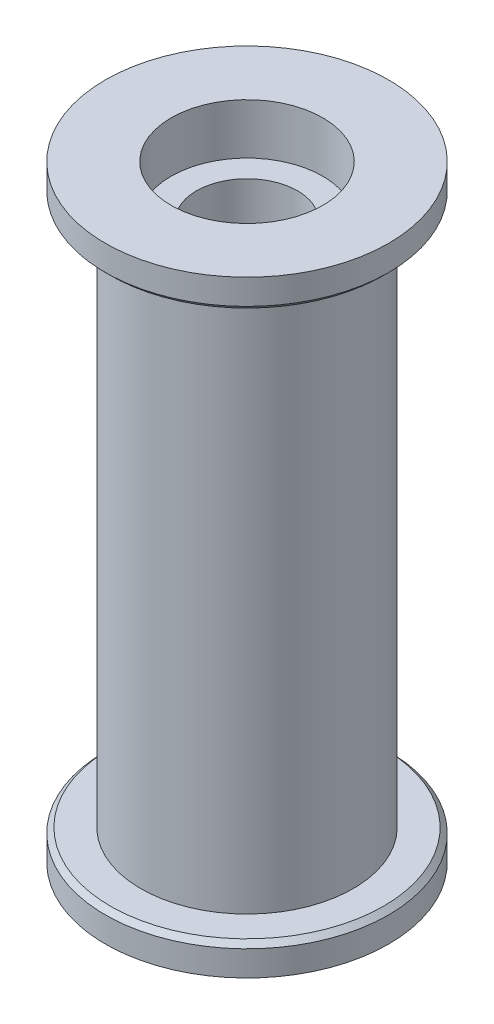
SolidWorks part; units mm, degrees
ref_plane "前视基准面" through (0, 0, 0) normal (0, 0, 1) x (1, 0, 0)
ref_plane "上视基准面" through (0, 0, 0) normal (0, 1, 0) x (1, 0, 0)
ref_plane "右视基准面" through (0, 0, 0) normal (1, 0, 0) x (0, 0, -1)
other "Configuration Table"
sketch "草图1" plane through (0, 0, 0) normal (0, 0, 1) x (1, 0, 0)
  line L8 (0, 0) -> (0, -60) construction
  line L9 (0, -60) -> (14, -60)
  line L10 (14, -60) -> (14, -57)
  line L11 (14, -57) -> (10.5, -57)
  line L12 (10.5, -57) -> (10.5, -3)
  line L13 (10.5, -3) -> (14, -3)
  line L14 (14, -3) -> (14, 0)
  line L15 (14, 0) -> (0, 0)
  line L16 (7.5, 0) -> (7.5, -5)
  line L17 (7.5, -5) -> (5, -5)
  line L18 (5, -5) -> (5, -55)
  line L19 (5, -55) -> (7.5, -55)
  line L20 (7.5, -55) -> (7.5, -60)
  dimension "D1" = 60
  dimension "D2" = 3
  dimension "D3" = 3
  dimension "D4" = 5
  dimension "D5" = 5
  dimension "D6" = 14
  dimension "D7" = 10.5
  dimension "D8" = 15
  dimension "D9" = 10
  dimension "D10" = 15
revolve "旋转1" add sketch "草图1" angle 360 about L8
chamfer "倒角1" distance 0.5 angle 45 2 edges at (-14, -57, 0) (-14, -3, 0)
